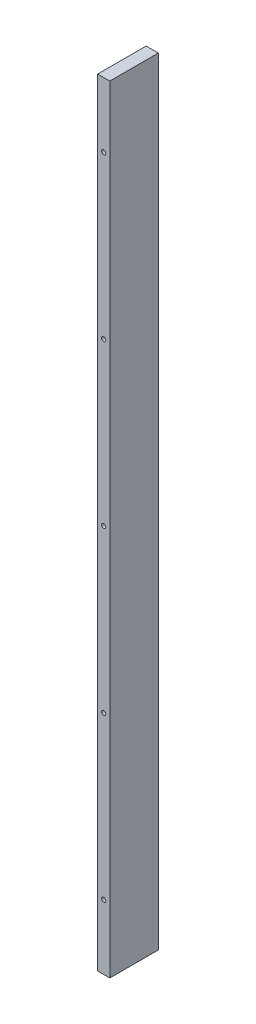
SolidWorks part; units mm, degrees
ref_plane "Front" through (0, 0, 0) normal (0, 0, 1) x (1, 0, 0)
ref_plane "Top" through (0, 0, 0) normal (0, 1, 0) x (1, 0, 0)
ref_plane "Right" through (0, 0, 0) normal (1, 0, 0) x (0, 0, -1)
sketch "Sketch1" plane through (0, 0, 0) normal (1, 0, 0) x (0, 0, -1)
  line L1 (0, 0) -> (76.2, 0)
  line L2 (0, 0) -> (0, 1219.2)
  line L3 (0, 1219.2) -> (76.2, 1219.2)
  line L4 (76.2, 0) -> (76.2, 1219.2)
  dimension "D1" = 76.2
  dimension "D2" = 1219.2
extrude "Extrude1" add sketch "Sketch1" along normal blind 19.05
hole_wizard "5/16-18 Tapped Hole1" positions "Sketch3" profile "Sketch2" tap size "5/16-18" standard "Ansi Inch"
sketch "Sketch3" plane through (0, 0, 0) normal (0, 0, 1) x (1, 0, 0)
  line L0 (0, 1219.2) -> (0, 0) construction
  line L1 (19.05, 0) -> (0, 0) construction
  point P0 (9.525, 1117.6)
  point P1 (9.525, 863.6)
  point P3 (9.525, 609.6)
  point P5 (9.525, 355.6)
  point P7 (9.525, 101.6)
  dimension "D1" = 9.525
  dimension "D2" = 101.6
  dimension "D3" = 254
  dimension "D4" = 508
  dimension "D5" = 762
  dimension "D6" = 1016
sketch "Sketch2" plane through (9.525, 1117.6, 0) normal (1, 0, 0) x (0, -1, 0)
  line L0 (0, 0) -> (0, 24.8211)
  line L1 (0, 24.8211) -> (3.2639, 22.86)
  line L2 (3.2639, 22.86) -> (3.2639, 0)
  line L5 (3.2639, 0) -> (0, 0)
  line L10 (0, 24.8211) -> (-3.2639, 22.86) construction
  line L11 (0, -6.35) -> (0, 107.95) construction
  dimension "Tap Drill Dia." = 6.5278
  dimension "Tap Drill Depth" = 22.86
  dimension "Drill Angle" = 118
cosmetic thread "Hole Thread1" parameters "D1"=16.002, "D2"=7.9375
cosmetic thread "Hole Thread2" parameters "D1"=16.002, "D2"=7.9375
cosmetic thread "Hole Thread3" parameters "D1"=16.002, "D2"=7.9375
cosmetic thread "Hole Thread4" parameters "D1"=16.002, "D2"=7.9375
cosmetic thread "Hole Thread5" parameters "D1"=16.002, "D2"=7.9375
hole_wizard "5/16-18 Tapped Hole2" positions "Sketch5" profile "Sketch4" tap size "5/16-18" standard "Ansi Inch"
sketch "Sketch5" plane through (0, 0, 0) normal (0, -1, 0) x (1, 0, 0)
  line L0 (0, 0) -> (0, -76.2) construction
  line L1 (19.05, 0) -> (0, 0) construction
  point P0 (9.525, -63.5)
  point P1 (9.525, -12.7)
  dimension "D1" = 9.525
  dimension "D2" = 12.7
  dimension "D3" = 50.8
sketch "Sketch4" plane through (9.525, 0, -63.5) normal (1, 0, 0) x (0, 0, -1)
  line L0 (0, 0) -> (0, 24.8211)
  line L1 (0, 24.8211) -> (3.2639, 22.86)
  line L2 (3.2639, 22.86) -> (3.2639, 0)
  line L5 (3.2639, 0) -> (0, 0)
  line L10 (0, 24.8211) -> (-3.2639, 22.86) construction
  line L11 (0, -6.35) -> (0, 107.95) construction
  dimension "Tap Drill Dia." = 6.5278
  dimension "Tap Drill Depth" = 22.86
  dimension "Drill Angle" = 118
cosmetic thread "Hole Thread6" parameters "D1"=16.002, "D2"=7.9375
cosmetic thread "Hole Thread7" parameters "D1"=16.002, "D2"=7.9375
